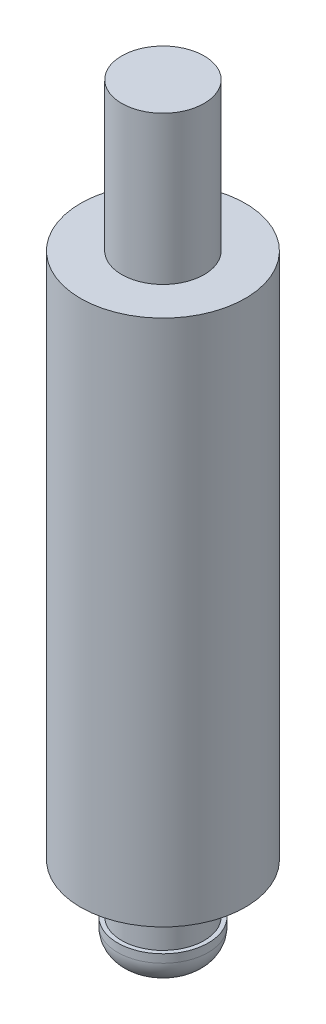
SolidWorks part; units mm, degrees
ref_plane "Front Plane" through (0, 0, 0) normal (0, 0, 1) x (1, 0, 0)
ref_plane "Top Plane" through (0, 0, 0) normal (0, 1, 0) x (1, 0, 0)
ref_plane "Right Plane" through (0, 0, 0) normal (1, 0, 0) x (0, 0, -1)
sketch "Sketch1" plane through (0, 0, 0) normal (0, 1, 0) x (1, 0, 0)
  circle A0 centre (0, 0) radius 2.5
  dimension "D1" = 5
extrude "Boss-Extrude1" add sketch "Sketch1" along normal blind 16 contours A0
sketch "Sketch2" plane through (0, 16, 0) normal (0, 1, 0) x (1, 0, 0)
  circle A0 centre (0, 0) radius 1.25
  dimension "D1" = 2.5
extrude "Boss-Extrude2" add sketch "Sketch2" along normal blind 4.5 contours A0
sketch "Sketch3" plane through (0, 0, 0) normal (0, -1, 0) x (-1, 0, 0)
  circle A0 centre (0, 0) radius 1.25
  dimension "D1" = 2.5
extrude "Boss-Extrude3" add sketch "Sketch3" along normal blind 1.5
sketch "Sketch4" plane through (0, -1.5, 0) normal (0, -1, 0) x (-1, 0, 0)
  circle A0 centre (0, 0) radius 1.375
  dimension "D1" = 2.75
extrude "Boss-Extrude4" add sketch "Sketch4" along normal blind 1
fillet "Fillet1" radius 0.75 1 edges at (0, -2.5, -1.375)
